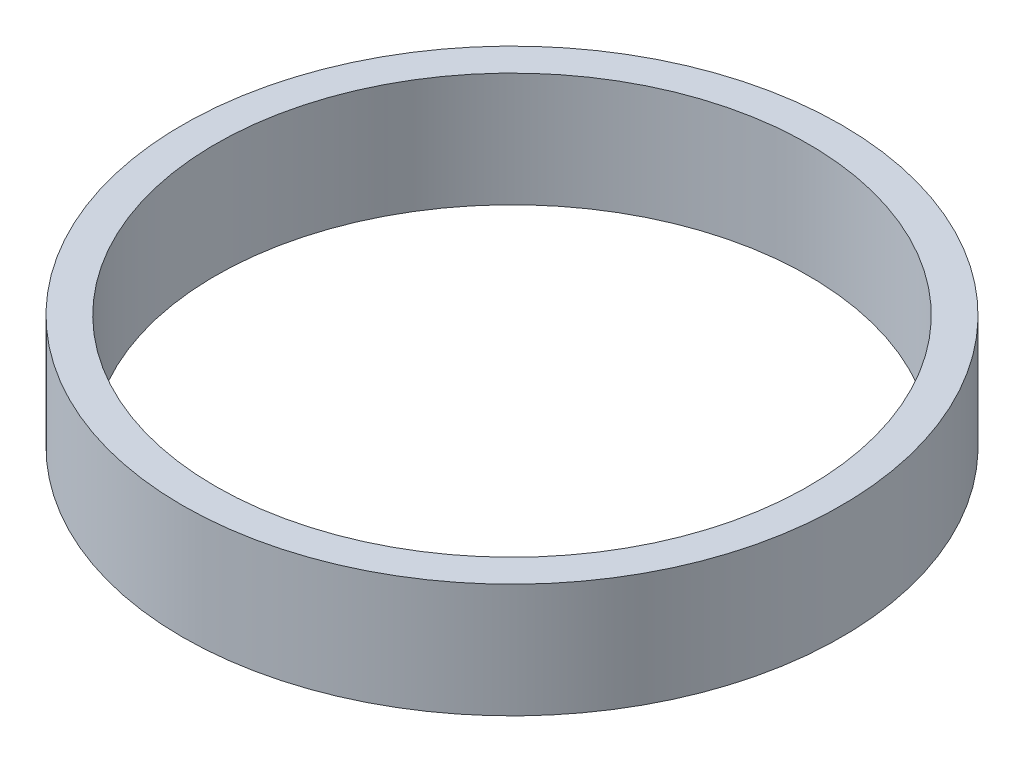
SolidWorks part; units mm, degrees
ref_plane "Front Plane" through (0, 0, 0) normal (0, 0, 1) x (1, 0, 0)
ref_plane "Top Plane" through (0, 0, 0) normal (0, 1, 0) x (1, 0, 0)
ref_plane "Right Plane" through (0, 0, 0) normal (1, 0, 0) x (0, 0, -1)
sketch "Sketch1" plane through (0, 0, 0) normal (0, 1, 0) x (1, 0, 0)
  circle A0 centre (0, 0) radius 26
  circle A1 centre (0, 0) radius 28.9
  dimension "D1" = 52
  dimension "D2" = 57.8
extrude "Boss-Extrude1" add sketch "Sketch1" along normal blind 10
